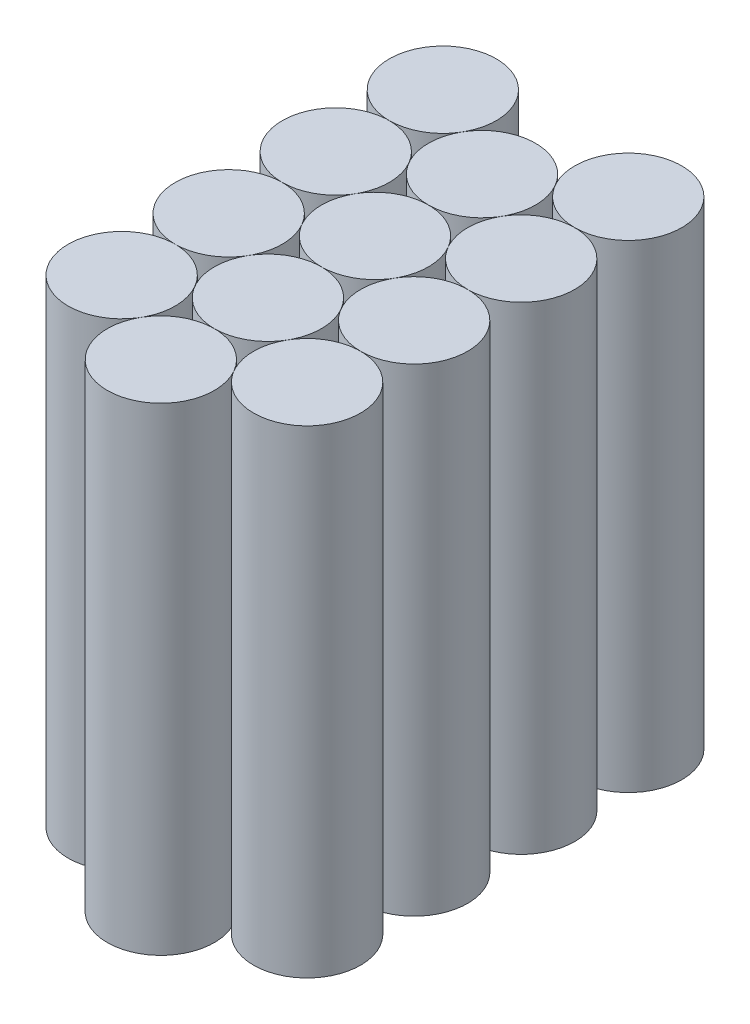
SolidWorks part; units mm, degrees
ref_plane "Front Plane" through (0, 0, 0) normal (0, 0, 1) x (1, 0, 0)
ref_plane "Top Plane" through (0, 0, 0) normal (0, 1, 0) x (1, 0, 0)
ref_plane "Right Plane" through (0, 0, 0) normal (1, 0, 0) x (0, 0, -1)
other "Center of Mass"
sketch "Sketch1" plane through (0, 0, 0) normal (0, 1, 0) x (1, 0, 0)
  line L0 (0, 0) -> (0, 83.4828) construction
  line L1 (-12.9904, -6.5589) -> (-12.9904, 106.0355) construction
  line L2 (12.9904, -6.5589) -> (12.9904, 106.0355) construction
  circle A0 centre (0, 0) radius 7.5
  circle A1 centre (0, 30) radius 7.5
  circle A2 centre (0, 45) radius 7.5
  circle A3 centre (0, 15) radius 7.5
  circle A8 centre (-12.9904, 7.5) radius 7.5
  circle A9 centre (-12.9904, 22.5) radius 7.5
  circle A10 centre (-12.9904, 37.5) radius 7.5
  circle A11 centre (-12.9904, 52.5) radius 7.5
  circle A12 centre (12.9904, 7.5) radius 7.5
  circle A13 centre (12.9904, 22.5) radius 7.5
  circle A14 centre (12.9904, 37.5) radius 7.5
  circle A15 centre (12.9904, 52.5) radius 7.5
  dimension "D1" = 15
extrude "Boss-Extrude1" add sketch "Sketch1" along normal blind 67 contours A12 | A0 | A3 | A8 | A9 | A10 | A11 | A2 | A1 | A15 | A14 | A13 A3
sketch "Sketch3" plane through (0, 0, 0) normal (0, 1, 0) x (1, 0, 0)
  line L0 (0, -8.6603) -> (20.4904, 3.1699)
  line L1 (-20.4904, 7.5) -> (20.4904, 7.5)
  line L6 (-20.4904, 3.1699) -> (0, -8.6603)
  line L7 (20.4904, 3.1699) -> (-20.4904, 3.1699)
  line L8 (20.4904, 3.1699) -> (20.4904, 60)
  line L9 (20.4904, 60) -> (-20.4904, 60)
  line L10 (-20.4904, 3.1699) -> (-20.4904, 60)
  line L11 (0, 3.1699) -> (0, -8.6603)
  line L12 (27.8967, 24.8397) -> (27.8967, -8.6603) construction
  circle A1 centre (-12.9904, 7.5) radius 7.5 construction
  circle A2 centre (12.9904, 7.5) radius 7.5 construction
  circle A4 centre (0, 0) radius 7.5 construction
  circle A5 centre (-12.9904, 52.5) radius 7.5 construction
  point P22 (0, 26.6767)
  dimension "D1" = 33.5
